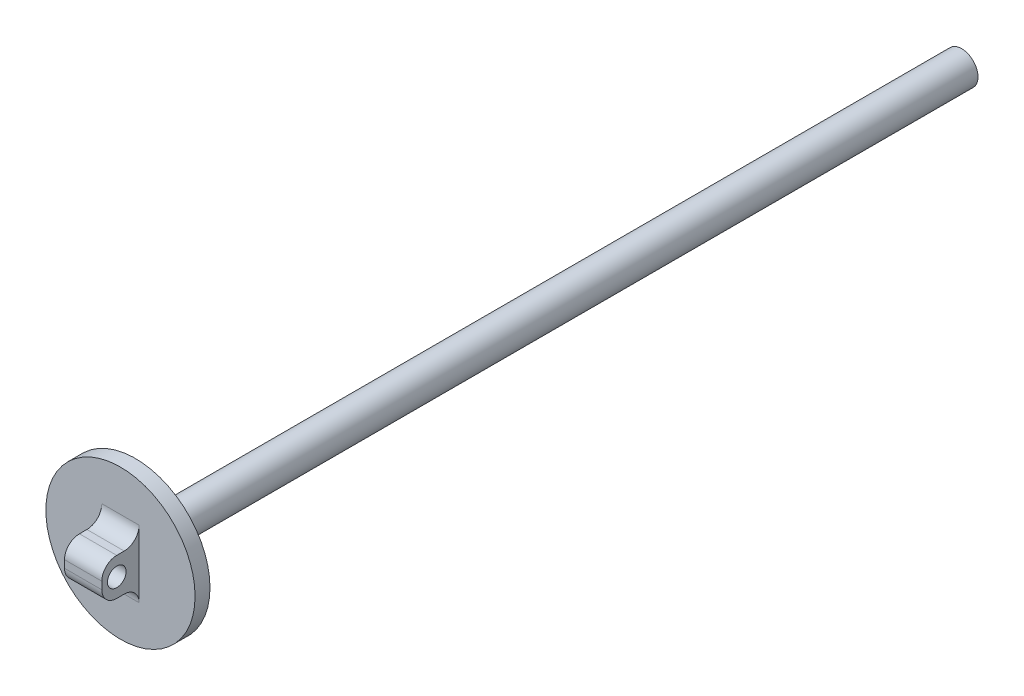
SolidWorks part; units mm, degrees
material "201 Annealed Stainless Steel (SS)"
ref_plane "Front Plane" through (0, 0, 0) normal (0, 0, 1) x (1, 0, 0)
ref_plane "Top Plane" through (0, 0, 0) normal (0, 1, 0) x (1, 0, 0)
ref_plane "Right Plane" through (0, 0, 0) normal (1, 0, 0) x (0, 0, -1)
sketch "Sketch1" plane through (0, 0, 0) normal (0, 0, 1) x (1, 0, 0)
  circle A0 centre (0, 0) radius 11.1125
  dimension "D1" = 22.225
extrude "Boss-Extrude1" add sketch "Sketch1" along normal blind 572.77
ref_plane "Plane1" through (0, 0, 572.77) normal (0, 0, 1) x (1, 0, 0)
sketch "Sketch2" plane through (0, 0, 572.77) normal (0, 0, 1) x (1, 0, 0)
  circle A0 centre (0, 0) radius 11.1125
  circle A1 centre (0, 0) radius 12.2617
  dimension "D1" = 22.225
  dimension "D2" = 24.5234
extrude "Boss-Extrude2" add sketch "Sketch2" against normal blind 25.4
sketch "Sketch6" plane through (0, 0, 572.77) normal (0, 0, 1) x (1, 0, 0)
  line L5 (-12.7, 12.7) -> (12.7, 12.7)
  line L6 (-12.7, 12.7) -> (-12.7, -12.7)
  line L11 (-12.7, -12.7) -> (12.7, -12.7)
  line L12 (12.7, 12.7) -> (12.7, -12.7)
  line L13 (-12.7, 12.7) -> (12.7, -12.7) construction
  line L14 (-12.7, -12.7) -> (12.7, 12.7) construction
  point P0 (0, 0)
  dimension "D1" = 25.4
  dimension "D2" = 25.4
extrude "Boss-Extrude3" add sketch "Sketch6" along normal blind 25.4
ref_plane "Plane2" through (12.7, 0, 0) normal (1, 0, 0) x (0, 0, -1)
sketch "Sketch7" plane through (12.7, 0, 0) normal (1, 0, 0) x (0, 0, -1)
  line L0 (-598.17, -12.7) -> (-598.17, 12.7) construction
  line L1 (-598.17, 0) -> (-588.01, 0) construction
  circle A0 centre (-588.01, 0) radius 6.35
  dimension "D1" = 12.7
  dimension "D2" = 10.16
extrude "Cut-Extrude1" cut sketch "Sketch7" against normal blind 50.8 contours A0
ref_plane "Plane3" through (0, 0, 572.77) normal (0, 0, 1) x (1, 0, 0)
sketch "Sketch8" plane through (0, 0, 572.77) normal (0, 0, 1) x (1, 0, 0)
  circle A0 centre (0, 0) radius 50.8
  dimension "D1" = 101.6
extrude "Boss-Extrude4" add sketch "Sketch8" against normal blind 10.16
ref_plane "Plane4" through (0, 0, 562.61) normal (0, 0, -1) x (-1, 0, 0)
sketch "Sketch9" plane through (0, 0, 562.61) normal (0, 0, -1) x (-1, 0, 0)
  circle A0 centre (0, 0) radius 44.45
  circle A1 centre (0, 0) radius 44.45
  dimension "D1" = 88.9
fillet "Fillet1" radius 10.16 4 edges at (0, -12.7, 572.77) (0, 12.7, 572.77) (0, 12.7, 598.17) (0, -12.7, 598.17)
